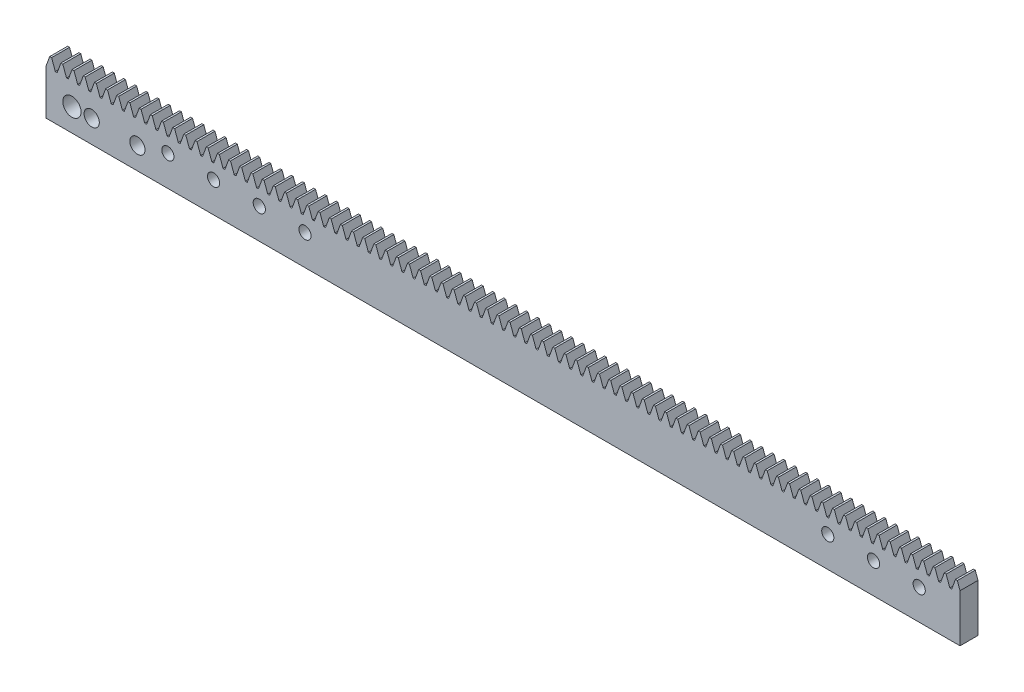
SolidWorks part; units mm, degrees
ref_plane "Alzado" through (0, 0, 0) normal (0, 0, 1) x (1, 0, 0)
ref_plane "Planta" through (0, 0, 0) normal (0, 1, 0) x (1, 0, 0)
ref_plane "Vista lateral" through (0, 0, 0) normal (1, 0, 0) x (0, 0, -1)
sketch "Croquis1" plane through (0, 0, 0) normal (0, 0, 1) x (1, 0, 0)
  line L0 (-152.812, 19.3115) -> (-151.5939, 22.6581)
  line L1 (186.6647, 22.6581) -> (186.0461, 22.6581)
  line L2 (182.9947, 22.6581) -> (182.3761, 22.6581)
  line L3 (-152.812, 4.5385) -> (188.488, 4.5385)
  line L4 (188.488, 19.3115) -> (188.488, 4.5385)
  line L5 (179.3247, 22.6581) -> (178.7061, 22.6581)
  line L6 (175.6547, 22.6581) -> (175.0361, 22.6581)
  line L7 (171.9847, 22.6581) -> (171.3661, 22.6581)
  line L8 (168.3147, 22.6581) -> (167.6961, 22.6581)
  line L9 (164.6447, 22.6581) -> (164.0261, 22.6581)
  line L10 (160.9747, 22.6581) -> (160.3561, 22.6581)
  line L11 (-149.142, 19.3115) -> (-147.9239, 22.6581)
  line L12 (-149.7573, 19.3115) -> (-150.9753, 22.6581)
  line L13 (-149.7573, 19.3115) -> (-149.1373, 19.3115)
  line L14 (157.3047, 22.6581) -> (156.6861, 22.6581)
  line L15 (153.6347, 22.6581) -> (153.0161, 22.6581)
  line L16 (-146.0873, 19.3115) -> (-147.3053, 22.6581)
  line L17 (-146.0873, 19.3115) -> (-145.4673, 19.3115)
  line L18 (-145.472, 19.3115) -> (-144.2539, 22.6581)
  line L19 (149.9647, 22.6581) -> (149.3461, 22.6581)
  line L20 (146.2947, 22.6581) -> (145.6761, 22.6581)
  line L21 (-142.4173, 19.3115) -> (-143.6353, 22.6581)
  line L22 (-142.4173, 19.3115) -> (-141.7973, 19.3115)
  line L23 (-141.802, 19.3115) -> (-140.5839, 22.6581)
  line L24 (142.6247, 22.6581) -> (142.0061, 22.6581)
  line L25 (138.9547, 22.6581) -> (138.3361, 22.6581)
  line L26 (-138.7473, 19.3115) -> (-139.9653, 22.6581)
  line L27 (-138.7473, 19.3115) -> (-138.1273, 19.3115)
  line L28 (-138.132, 19.3115) -> (-136.9139, 22.6581)
  line L29 (135.2847, 22.6581) -> (134.5139, 22.6581)
  line L30 (131.6147, 22.6581) -> (130.9961, 22.6581)
  line L31 (-135.0773, 19.3115) -> (-136.2953, 22.6581)
  line L32 (-135.0773, 19.3115) -> (-134.4573, 19.3115)
  line L33 (-134.462, 19.3115) -> (-133.2439, 22.6581)
  line L34 (127.9447, 22.6581) -> (127.3261, 22.6581)
  line L35 (124.2747, 22.6581) -> (123.6561, 22.6581)
  line L36 (-131.4073, 19.3115) -> (-132.6253, 22.6581)
  line L37 (-131.4073, 19.3115) -> (-130.7873, 19.3115)
  line L38 (-130.792, 19.3115) -> (-129.5739, 22.6581)
  line L39 (120.6047, 22.6581) -> (119.9861, 22.6581)
  line L40 (116.9347, 22.6581) -> (116.3161, 22.6581)
  line L41 (-127.7373, 19.3115) -> (-128.9553, 22.6581)
  line L42 (-127.7373, 19.3115) -> (-127.1173, 19.3115)
  line L43 (-127.122, 19.3115) -> (-125.9039, 22.6581)
  line L44 (113.2647, 22.6581) -> (112.6461, 22.6581)
  line L45 (109.5947, 22.6581) -> (108.9761, 22.6581)
  line L46 (-124.0673, 19.3115) -> (-125.2853, 22.6581)
  line L47 (-124.0673, 19.3115) -> (-123.4473, 19.3115)
  line L48 (-123.452, 19.3115) -> (-122.2339, 22.6581)
  line L49 (105.9247, 22.6581) -> (105.3061, 22.6581)
  line L50 (102.2547, 22.6581) -> (101.6361, 22.6581)
  line L51 (-120.3973, 19.3115) -> (-121.6153, 22.6581)
  line L52 (-120.3973, 19.3115) -> (-119.7773, 19.3115)
  line L53 (-119.782, 19.3115) -> (-118.5639, 22.6581)
  line L54 (98.5847, 22.6581) -> (97.9661, 22.6581)
  line L55 (94.9147, 22.6581) -> (94.2961, 22.6581)
  line L56 (-116.7273, 19.3115) -> (-117.9453, 22.6581)
  line L57 (-116.7273, 19.3115) -> (-116.1073, 19.3115)
  line L58 (-116.112, 19.3115) -> (-114.8939, 22.6581)
  line L59 (91.2447, 22.6581) -> (90.6261, 22.6581)
  line L60 (87.5747, 22.6581) -> (86.9561, 22.6581)
  line L61 (-113.0573, 19.3115) -> (-114.2753, 22.6581)
  line L62 (-113.0573, 19.3115) -> (-112.4373, 19.3115)
  line L63 (-112.442, 19.3115) -> (-111.2239, 22.6581)
  line L64 (83.9047, 22.6581) -> (83.2861, 22.6581)
  line L65 (80.2347, 22.6581) -> (79.6161, 22.6581)
  line L66 (-109.3873, 19.3115) -> (-110.6053, 22.6581)
  line L67 (-109.3873, 19.3115) -> (-108.7673, 19.3115)
  line L68 (-108.772, 19.3115) -> (-107.5539, 22.6581)
  line L69 (76.5647, 22.6581) -> (75.9461, 22.6581)
  line L70 (72.8947, 22.6581) -> (72.2761, 22.6581)
  line L71 (-105.7173, 19.3115) -> (-106.9353, 22.6581)
  line L72 (-105.7173, 19.3115) -> (-105.0973, 19.3115)
  line L73 (-105.102, 19.3115) -> (-103.8839, 22.6581)
  line L74 (69.2247, 22.6581) -> (68.6061, 22.6581)
  line L75 (65.5547, 22.6581) -> (64.9361, 22.6581)
  line L76 (-102.0473, 19.3115) -> (-103.2653, 22.6581)
  line L77 (-102.0473, 19.3115) -> (-101.4273, 19.3115)
  line L78 (-101.432, 19.3115) -> (-100.2139, 22.6581)
  line L79 (61.8847, 22.6581) -> (61.2661, 22.6581)
  line L80 (58.2147, 22.6581) -> (57.5961, 22.6581)
  line L81 (-98.3773, 19.3115) -> (-99.5953, 22.6581)
  line L82 (-98.3773, 19.3115) -> (-97.7573, 19.3115)
  line L83 (-97.762, 19.3115) -> (-96.5439, 22.6581)
  line L84 (54.5447, 22.6581) -> (53.9261, 22.6581)
  line L85 (50.8747, 22.6581) -> (50.2561, 22.6581)
  line L86 (-94.7073, 19.3115) -> (-95.9253, 22.6581)
  line L87 (-94.7073, 19.3115) -> (-94.0873, 19.3115)
  line L88 (-94.092, 19.3115) -> (-92.8739, 22.6581)
  line L89 (47.2047, 22.6581) -> (46.5861, 22.6581)
  line L90 (43.5347, 22.6581) -> (42.9161, 22.6581)
  line L91 (-91.0373, 19.3115) -> (-92.2553, 22.6581)
  line L92 (-91.0373, 19.3115) -> (-90.4173, 19.3115)
  line L93 (-90.422, 19.3115) -> (-89.2039, 22.6581)
  line L94 (39.8647, 22.6581) -> (39.2461, 22.6581)
  line L95 (36.1947, 22.6581) -> (35.5761, 22.6581)
  line L96 (-87.3673, 19.3115) -> (-88.5853, 22.6581)
  line L97 (-87.3673, 19.3115) -> (-86.7473, 19.3115)
  line L98 (-86.752, 19.3115) -> (-85.5339, 22.6581)
  line L99 (32.5247, 22.6581) -> (31.9061, 22.6581)
  line L100 (28.8547, 22.6581) -> (28.2361, 22.6581)
  line L101 (-83.6973, 19.3115) -> (-84.9153, 22.6581)
  line L102 (-83.6973, 19.3115) -> (-83.0773, 19.3115)
  line L103 (-83.082, 19.3115) -> (-81.8639, 22.6581)
  line L104 (25.1847, 22.6581) -> (24.5661, 22.6581)
  line L105 (21.5147, 22.6581) -> (20.8961, 22.6581)
  line L106 (-80.0273, 19.3115) -> (-81.2453, 22.6581)
  line L107 (-80.0273, 19.3115) -> (-79.4073, 19.3115)
  line L108 (-79.412, 19.3115) -> (-78.1939, 22.6581)
  line L109 (17.8447, 22.6581) -> (17.2261, 22.6581)
  line L110 (14.1747, 22.6581) -> (13.5561, 22.6581)
  line L111 (-76.3573, 19.3115) -> (-77.5753, 22.6581)
  line L112 (-76.3573, 19.3115) -> (-75.7373, 19.3115)
  line L113 (-75.742, 19.3115) -> (-74.5239, 22.6581)
  line L114 (10.5047, 22.6581) -> (9.8861, 22.6581)
  line L115 (6.8347, 22.6581) -> (6.2161, 22.6581)
  line L116 (-72.6873, 19.3115) -> (-73.9053, 22.6581)
  line L117 (-72.6873, 19.3115) -> (-72.0673, 19.3115)
  line L118 (-72.072, 19.3115) -> (-70.8539, 22.6581)
  line L119 (3.1647, 22.6581) -> (2.5461, 22.6581)
  line L120 (-0.5053, 22.6581) -> (-1.1239, 22.6581)
  line L121 (-69.0173, 19.3115) -> (-70.2353, 22.6581)
  line L122 (-69.0173, 19.3115) -> (-68.3973, 19.3115)
  line L123 (-68.402, 19.3115) -> (-67.1839, 22.6581)
  line L124 (-4.1753, 22.6581) -> (-4.7939, 22.6581)
  line L125 (-7.8453, 22.6581) -> (-8.4639, 22.6581)
  line L126 (-65.3473, 19.3115) -> (-66.5653, 22.6581)
  line L127 (-65.3473, 19.3115) -> (-64.7273, 19.3115)
  line L128 (-64.732, 19.3115) -> (-63.5139, 22.6581)
  line L129 (-11.5153, 22.6581) -> (-12.1339, 22.6581)
  line L130 (-15.1853, 22.6581) -> (-15.8039, 22.6581)
  line L131 (-61.6773, 19.3115) -> (-62.8953, 22.6581)
  line L132 (-61.6773, 19.3115) -> (-61.0573, 19.3115)
  line L133 (-61.062, 19.3115) -> (-59.8439, 22.6581)
  line L134 (-18.8553, 22.6581) -> (-19.4739, 22.6581)
  line L135 (-22.5253, 22.6581) -> (-23.1439, 22.6581)
  line L136 (-58.0073, 19.3115) -> (-59.2253, 22.6581)
  line L137 (-58.0073, 19.3115) -> (-57.3873, 19.3115)
  line L138 (-57.392, 19.3115) -> (-56.1739, 22.6581)
  line L139 (-26.1953, 22.6581) -> (-26.8139, 22.6581)
  line L140 (-29.8653, 22.6581) -> (-30.4839, 22.6581)
  line L141 (-54.3373, 19.3115) -> (-55.5553, 22.6581)
  line L142 (-54.3373, 19.3115) -> (-53.7173, 19.3115)
  line L143 (-53.722, 19.3115) -> (-52.5039, 22.6581)
  line L144 (-33.5353, 22.6581) -> (-34.1539, 22.6581)
  line L145 (-37.2053, 22.6581) -> (-37.8239, 22.6581)
  line L146 (-50.6673, 19.3115) -> (-51.8853, 22.6581)
  line L147 (-50.6673, 19.3115) -> (-50.0473, 19.3115)
  line L148 (-50.052, 19.3115) -> (-48.8339, 22.6581)
  line L149 (-40.8753, 22.6581) -> (-41.4939, 22.6581)
  line L150 (-44.5453, 22.6581) -> (-45.1639, 22.6581)
  line L151 (-46.9973, 19.3115) -> (-48.2153, 22.6581)
  line L152 (-46.9973, 19.3115) -> (-46.3773, 19.3115)
  line L153 (-46.382, 19.3115) -> (-45.1639, 22.6581)
  line L154 (-48.2153, 22.6581) -> (-48.8339, 22.6581)
  line L155 (-51.8853, 22.6581) -> (-52.5039, 22.6581)
  line L156 (-43.3273, 19.3115) -> (-44.5453, 22.6581)
  line L157 (-43.3273, 19.3115) -> (-42.7073, 19.3115)
  line L158 (-42.712, 19.3115) -> (-41.4939, 22.6581)
  line L159 (-55.5553, 22.6581) -> (-56.1739, 22.6581)
  line L160 (-59.2253, 22.6581) -> (-59.8439, 22.6581)
  line L161 (-39.6573, 19.3115) -> (-40.8753, 22.6581)
  line L162 (-39.6573, 19.3115) -> (-39.0373, 19.3115)
  line L163 (-39.042, 19.3115) -> (-37.8239, 22.6581)
  line L164 (-62.8953, 22.6581) -> (-63.5139, 22.6581)
  line L165 (-66.5653, 22.6581) -> (-67.1839, 22.6581)
  line L166 (-35.9873, 19.3115) -> (-37.2053, 22.6581)
  line L167 (-35.9873, 19.3115) -> (-35.3673, 19.3115)
  line L168 (-35.372, 19.3115) -> (-34.1539, 22.6581)
  line L169 (-70.2353, 22.6581) -> (-70.8539, 22.6581)
  line L170 (-73.9053, 22.6581) -> (-74.5239, 22.6581)
  line L171 (-32.3173, 19.3115) -> (-33.5353, 22.6581)
  line L172 (-32.3173, 19.3115) -> (-31.6973, 19.3115)
  line L173 (-31.702, 19.3115) -> (-30.4839, 22.6581)
  line L174 (-77.5753, 22.6581) -> (-78.1939, 22.6581)
  line L175 (-81.2453, 22.6581) -> (-81.8639, 22.6581)
  line L176 (-28.6473, 19.3115) -> (-29.8653, 22.6581)
  line L177 (-28.6473, 19.3115) -> (-28.0273, 19.3115)
  line L178 (-28.032, 19.3115) -> (-26.8139, 22.6581)
  line L179 (-84.9153, 22.6581) -> (-85.5339, 22.6581)
  line L180 (-88.5853, 22.6581) -> (-89.2039, 22.6581)
  line L181 (-24.9773, 19.3115) -> (-26.1953, 22.6581)
  line L182 (-24.9773, 19.3115) -> (-24.3573, 19.3115)
  line L183 (-24.362, 19.3115) -> (-23.1439, 22.6581)
  line L184 (-92.2553, 22.6581) -> (-92.8739, 22.6581)
  line L185 (-95.9253, 22.6581) -> (-96.5439, 22.6581)
  line L186 (-21.3073, 19.3115) -> (-22.5253, 22.6581)
  line L187 (-21.3073, 19.3115) -> (-20.6873, 19.3115)
  line L188 (-20.692, 19.3115) -> (-19.4739, 22.6581)
  line L189 (-99.5953, 22.6581) -> (-100.2139, 22.6581)
  line L190 (-103.2653, 22.6581) -> (-103.8839, 22.6581)
  line L191 (-17.6373, 19.3115) -> (-18.8553, 22.6581)
  line L192 (-17.6373, 19.3115) -> (-17.0173, 19.3115)
  line L193 (-17.022, 19.3115) -> (-15.8039, 22.6581)
  line L194 (-106.9353, 22.6581) -> (-107.5539, 22.6581)
  line L195 (-110.6053, 22.6581) -> (-111.2239, 22.6581)
  line L196 (-13.9673, 19.3115) -> (-15.1853, 22.6581)
  line L197 (-13.9673, 19.3115) -> (-13.3473, 19.3115)
  line L198 (-13.352, 19.3115) -> (-12.1339, 22.6581)
  line L199 (-114.2753, 22.6581) -> (-114.8939, 22.6581)
  line L200 (-117.9453, 22.6581) -> (-118.5639, 22.6581)
  line L201 (-10.2973, 19.3115) -> (-11.5153, 22.6581)
  line L202 (-10.2973, 19.3115) -> (-9.6773, 19.3115)
  line L203 (-9.682, 19.3115) -> (-8.4639, 22.6581)
  line L204 (-121.6153, 22.6581) -> (-122.2339, 22.6581)
  line L205 (-125.2853, 22.6581) -> (-125.9039, 22.6581)
  line L206 (-6.6273, 19.3115) -> (-7.8453, 22.6581)
  line L207 (-6.6273, 19.3115) -> (-6.0073, 19.3115)
  line L208 (-6.012, 19.3115) -> (-4.7939, 22.6581)
  line L209 (-128.9553, 22.6581) -> (-129.5739, 22.6581)
  line L210 (-132.6253, 22.6581) -> (-133.2439, 22.6581)
  line L211 (-2.9573, 19.3115) -> (-4.1753, 22.6581)
  line L212 (-2.9573, 19.3115) -> (-2.3373, 19.3115)
  line L213 (-2.342, 19.3115) -> (-1.1239, 22.6581)
  line L214 (-136.2953, 22.6581) -> (-136.9139, 22.6581)
  line L215 (-139.9653, 22.6581) -> (-140.5839, 22.6581)
  line L216 (0.7127, 19.3115) -> (-0.5053, 22.6581)
  line L217 (0.7127, 19.3115) -> (1.3327, 19.3115)
  line L218 (1.328, 19.3115) -> (2.5461, 22.6581)
  line L219 (-147.3053, 22.6581) -> (-147.9239, 22.6581)
  line L220 (-150.9753, 22.6581) -> (-151.5939, 22.6581)
  line L221 (4.3827, 19.3115) -> (3.1647, 22.6581)
  line L222 (4.3827, 19.3115) -> (5.0027, 19.3115)
  line L223 (4.998, 19.3115) -> (6.2161, 22.6581)
  line L224 (-152.812, 19.3115) -> (-152.812, 4.5385)
  line L226 (8.0527, 19.3115) -> (6.8347, 22.6581)
  line L227 (8.0527, 19.3115) -> (8.6727, 19.3115)
  line L228 (8.668, 19.3115) -> (9.8861, 22.6581)
  line L231 (11.7227, 19.3115) -> (10.5047, 22.6581)
  line L232 (11.7227, 19.3115) -> (12.3427, 19.3115)
  line L233 (12.338, 19.3115) -> (13.5561, 22.6581)
  line L236 (15.3927, 19.3115) -> (14.1747, 22.6581)
  line L237 (15.3927, 19.3115) -> (16.0127, 19.3115)
  line L238 (16.008, 19.3115) -> (17.2261, 22.6581)
  line L241 (19.0627, 19.3115) -> (17.8447, 22.6581)
  line L242 (19.0627, 19.3115) -> (19.6827, 19.3115)
  line L243 (19.678, 19.3115) -> (20.8961, 22.6581)
  line L246 (22.7327, 19.3115) -> (21.5147, 22.6581)
  line L247 (22.7327, 19.3115) -> (23.3527, 19.3115)
  line L248 (23.348, 19.3115) -> (24.5661, 22.6581)
  line L251 (26.4027, 19.3115) -> (25.1847, 22.6581)
  line L252 (26.4027, 19.3115) -> (27.0227, 19.3115)
  line L253 (27.018, 19.3115) -> (28.2361, 22.6581)
  line L256 (30.0727, 19.3115) -> (28.8547, 22.6581)
  line L257 (30.0727, 19.3115) -> (30.6927, 19.3115)
  line L258 (30.688, 19.3115) -> (31.9061, 22.6581)
  line L261 (33.7427, 19.3115) -> (32.5247, 22.6581)
  line L262 (33.7427, 19.3115) -> (34.3627, 19.3115)
  line L263 (34.358, 19.3115) -> (35.5761, 22.6581)
  line L266 (37.4127, 19.3115) -> (36.1947, 22.6581)
  line L267 (37.4127, 19.3115) -> (38.0327, 19.3115)
  line L268 (38.028, 19.3115) -> (39.2461, 22.6581)
  line L271 (41.0827, 19.3115) -> (39.8647, 22.6581)
  line L272 (41.0827, 19.3115) -> (41.7027, 19.3115)
  line L273 (41.698, 19.3115) -> (42.9161, 22.6581)
  line L276 (44.7527, 19.3115) -> (43.5347, 22.6581)
  line L277 (44.7527, 19.3115) -> (45.3727, 19.3115)
  line L278 (45.368, 19.3115) -> (46.5861, 22.6581)
  line L281 (48.4227, 19.3115) -> (47.2047, 22.6581)
  line L282 (48.4227, 19.3115) -> (49.0427, 19.3115)
  line L283 (49.038, 19.3115) -> (50.2561, 22.6581)
  line L286 (52.0927, 19.3115) -> (50.8747, 22.6581)
  line L287 (52.0927, 19.3115) -> (52.7127, 19.3115)
  line L288 (52.708, 19.3115) -> (53.9261, 22.6581)
  line L291 (55.7627, 19.3115) -> (54.5447, 22.6581)
  line L292 (55.7627, 19.3115) -> (56.3827, 19.3115)
  line L293 (56.378, 19.3115) -> (57.5961, 22.6581)
  line L296 (59.4327, 19.3115) -> (58.2147, 22.6581)
  line L297 (59.4327, 19.3115) -> (60.0527, 19.3115)
  line L298 (60.048, 19.3115) -> (61.2661, 22.6581)
  line L301 (63.1027, 19.3115) -> (61.8847, 22.6581)
  line L302 (63.1027, 19.3115) -> (63.7227, 19.3115)
  line L303 (63.718, 19.3115) -> (64.9361, 22.6581)
  line L306 (66.7727, 19.3115) -> (65.5547, 22.6581)
  line L307 (66.7727, 19.3115) -> (67.3927, 19.3115)
  line L308 (67.388, 19.3115) -> (68.6061, 22.6581)
  line L311 (70.4427, 19.3115) -> (69.2247, 22.6581)
  line L312 (70.4427, 19.3115) -> (71.0627, 19.3115)
  line L313 (71.058, 19.3115) -> (72.2761, 22.6581)
  line L316 (74.1127, 19.3115) -> (72.8947, 22.6581)
  line L317 (74.1127, 19.3115) -> (74.7327, 19.3115)
  line L318 (74.728, 19.3115) -> (75.9461, 22.6581)
  line L321 (77.7827, 19.3115) -> (76.5647, 22.6581)
  line L322 (77.7827, 19.3115) -> (78.4027, 19.3115)
  line L323 (78.398, 19.3115) -> (79.6161, 22.6581)
  line L326 (81.4527, 19.3115) -> (80.2347, 22.6581)
  line L327 (81.4527, 19.3115) -> (82.0727, 19.3115)
  line L328 (82.068, 19.3115) -> (83.2861, 22.6581)
  line L331 (85.1227, 19.3115) -> (83.9047, 22.6581)
  line L332 (85.1227, 19.3115) -> (85.7427, 19.3115)
  line L333 (85.738, 19.3115) -> (86.9561, 22.6581)
  line L336 (88.7927, 19.3115) -> (87.5747, 22.6581)
  line L337 (88.7927, 19.3115) -> (89.4127, 19.3115)
  line L338 (89.408, 19.3115) -> (90.6261, 22.6581)
  line L341 (92.4627, 19.3115) -> (91.2447, 22.6581)
  line L342 (92.4627, 19.3115) -> (93.0827, 19.3115)
  line L343 (93.078, 19.3115) -> (94.2961, 22.6581)
  line L346 (96.1327, 19.3115) -> (94.9147, 22.6581)
  line L347 (96.1327, 19.3115) -> (96.7527, 19.3115)
  line L348 (96.748, 19.3115) -> (97.9661, 22.6581)
  line L351 (99.8027, 19.3115) -> (98.5847, 22.6581)
  line L352 (99.8027, 19.3115) -> (100.4227, 19.3115)
  line L353 (100.418, 19.3115) -> (101.6361, 22.6581)
  line L356 (103.4727, 19.3115) -> (102.2547, 22.6581)
  line L357 (103.4727, 19.3115) -> (104.0927, 19.3115)
  line L358 (104.088, 19.3115) -> (105.3061, 22.6581)
  line L361 (107.1427, 19.3115) -> (105.9247, 22.6581)
  line L362 (107.1427, 19.3115) -> (107.7627, 19.3115)
  line L363 (107.758, 19.3115) -> (108.9761, 22.6581)
  line L366 (110.8127, 19.3115) -> (109.5947, 22.6581)
  line L367 (110.8127, 19.3115) -> (111.4327, 19.3115)
  line L368 (111.428, 19.3115) -> (112.6461, 22.6581)
  line L371 (114.4827, 19.3115) -> (113.2647, 22.6581)
  line L372 (114.4827, 19.3115) -> (115.1027, 19.3115)
  line L373 (115.098, 19.3115) -> (116.3161, 22.6581)
  line L376 (118.1527, 19.3115) -> (116.9347, 22.6581)
  line L377 (118.1527, 19.3115) -> (118.7727, 19.3115)
  line L378 (118.768, 19.3115) -> (119.9861, 22.6581)
  line L381 (121.8227, 19.3115) -> (120.6047, 22.6581)
  line L382 (121.8227, 19.3115) -> (122.4427, 19.3115)
  line L383 (122.438, 19.3115) -> (123.6561, 22.6581)
  line L386 (125.4927, 19.3115) -> (124.2747, 22.6581)
  line L387 (125.4927, 19.3115) -> (126.1127, 19.3115)
  line L388 (126.108, 19.3115) -> (127.3261, 22.6581)
  line L391 (129.1627, 19.3115) -> (127.9447, 22.6581)
  line L392 (129.1627, 19.3115) -> (129.7827, 19.3115)
  line L393 (129.778, 19.3115) -> (130.9961, 22.6581)
  line L396 (132.8327, 19.3115) -> (131.6147, 22.6581)
  line L397 (132.8327, 19.3115) -> (133.4527, 19.3115)
  line L398 (133.448, 19.3115) -> (134.6661, 22.6581)
  line L401 (136.5027, 19.3115) -> (135.2847, 22.6581)
  line L402 (136.5027, 19.3115) -> (137.1227, 19.3115)
  line L403 (137.118, 19.3115) -> (138.3361, 22.6581)
  line L406 (140.1727, 19.3115) -> (138.9547, 22.6581)
  line L407 (140.1727, 19.3115) -> (140.7927, 19.3115)
  line L408 (140.788, 19.3115) -> (142.0061, 22.6581)
  line L411 (143.8427, 19.3115) -> (142.6247, 22.6581)
  line L412 (143.8427, 19.3115) -> (144.4627, 19.3115)
  line L413 (144.458, 19.3115) -> (145.6761, 22.6581)
  line L416 (147.5127, 19.3115) -> (146.2947, 22.6581)
  line L417 (147.5127, 19.3115) -> (148.1327, 19.3115)
  line L418 (148.128, 19.3115) -> (149.3461, 22.6581)
  line L421 (151.1827, 19.3115) -> (149.9647, 22.6581)
  line L422 (151.1827, 19.3115) -> (151.8027, 19.3115)
  line L423 (151.798, 19.3115) -> (153.0161, 22.6581)
  line L426 (154.8527, 19.3115) -> (153.6347, 22.6581)
  line L427 (154.8527, 19.3115) -> (155.4727, 19.3115)
  line L428 (155.468, 19.3115) -> (156.6861, 22.6581)
  line L431 (158.5227, 19.3115) -> (157.3047, 22.6581)
  line L432 (158.5227, 19.3115) -> (159.1427, 19.3115)
  line L433 (159.138, 19.3115) -> (160.3561, 22.6581)
  line L436 (162.1927, 19.3115) -> (160.9747, 22.6581)
  line L437 (162.1927, 19.3115) -> (162.8127, 19.3115)
  line L438 (162.808, 19.3115) -> (164.0261, 22.6581)
  line L441 (165.8627, 19.3115) -> (164.6447, 22.6581)
  line L442 (165.8627, 19.3115) -> (166.4827, 19.3115)
  line L443 (166.478, 19.3115) -> (167.6961, 22.6581)
  line L446 (169.5327, 19.3115) -> (168.3147, 22.6581)
  line L447 (169.5327, 19.3115) -> (170.1527, 19.3115)
  line L448 (170.148, 19.3115) -> (171.3661, 22.6581)
  line L451 (173.2027, 19.3115) -> (171.9847, 22.6581)
  line L452 (173.2027, 19.3115) -> (173.8227, 19.3115)
  line L453 (173.818, 19.3115) -> (175.0361, 22.6581)
  line L456 (176.8727, 19.3115) -> (175.6547, 22.6581)
  line L457 (176.8727, 19.3115) -> (177.4927, 19.3115)
  line L458 (177.488, 19.3115) -> (178.7061, 22.6581)
  line L461 (180.5427, 19.3115) -> (179.3247, 22.6581)
  line L462 (180.5427, 19.3115) -> (181.1627, 19.3115)
  line L463 (181.158, 19.3115) -> (182.3761, 22.6581)
  line L466 (184.2127, 19.3115) -> (182.9947, 22.6581)
  line L467 (184.2127, 19.3115) -> (184.8327, 19.3115)
  line L468 (184.828, 19.3115) -> (186.0461, 22.6581)
  line L471 (187.8827, 19.3115) -> (186.6647, 22.6581)
  line L472 (187.8827, 19.3115) -> (188.5027, 19.3115)
  circle A0 centre (-144.312, 12.0385) radius 3
  circle A1 centre (-112.812, 14.5385) radius 2
  arc A2 (-143.6353, 22.6581) -> (-144.2539, 22.6581) centre (-143.9446, 23.5079) cw
  dimension "D5" = 10
  dimension "D1" = 341.3
  dimension "D2" = 40
  dimension "D4" = 7.5
  dimension "D6" = 93
extrude "Saliente-Extruir1" add sketch "Croquis1" along normal blind 5.9
sketch "Croquis2" plane through (0, 0, 0) normal (0, 0, 1) x (1, 0, 0)
  line L0 (-152.812, 4.5385) -> (188.488, 4.5385) construction
  line L1 (-152.812, 19.3115) -> (-152.812, 4.5385) construction
  line L3 (147.188, -5.7946) -> (272.2377, -5.7946)
  line L4 (147.188, -5.7946) -> (147.188, 38.8211)
  line L5 (147.188, 38.8211) -> (272.2377, 38.8211)
  line L6 (272.2377, -5.7946) -> (272.2377, 38.8211)
  circle A0 centre (-137.812, 12.0385) radius 2.5
  circle A1 centre (-122.812, 11.7581) radius 2.5
  circle A2 centre (-97.812, 14.5385) radius 2
  circle A3 centre (-82.812, 14.5385) radius 2
  circle A4 centre (-67.812, 14.5385) radius 2
  circle A5 centre (-112.812, 14.5385) radius 2
  circle A6 centre (-144.312, 12.0385) radius 3
  circle A9 centre (103.788, 14.5385) radius 2
  circle A10 centre (118.788, 14.5385) radius 2
  circle A11 centre (133.788, 14.5385) radius 2
  dimension "D1" = 7.5
  dimension "D3" = 30
  dimension "D4" = 15
  dimension "D6" = 4
  dimension "D7" = 6
  dimension "D2" = 15
  dimension "D8" = 300
  dimension "D5" = 3
extrude "Cortar-Extruir2" cut sketch "Croquis2" along normal blind 16
